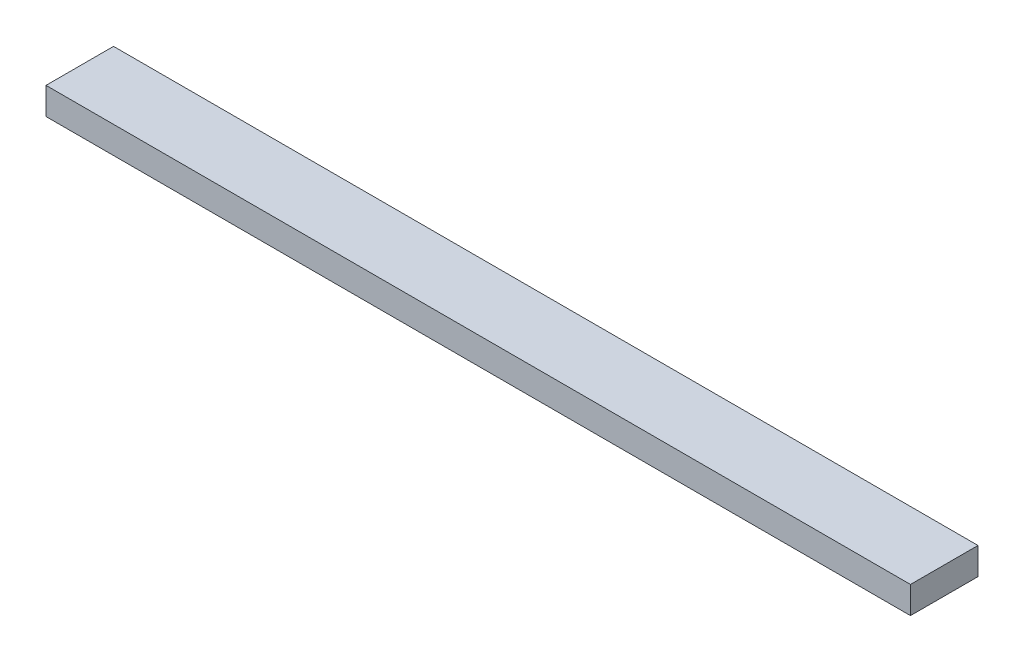
SolidWorks part; units mm, degrees
ref_plane "Front Plane" through (0, 0, 0) normal (0, 0, 1) x (1, 0, 0)
ref_plane "Top Plane" through (0, 0, 0) normal (0, 1, 0) x (1, 0, 0)
ref_plane "Right Plane" through (0, 0, 0) normal (1, 0, 0) x (0, 0, -1)
sketch "Sketch1" plane through (0, 0, 0) normal (0, 1, 0) x (1, 0, 0)
  line L1 (0, 0) -> (320, 0)
  line L2 (0, 0) -> (0, 25)
  line L3 (0, 25) -> (320, 25)
  line L4 (320, 0) -> (320, 25)
  dimension "D1" = 320
  dimension "D2" = 25
extrude "Boss-Extrude1" add sketch "Sketch1" along normal blind 10
